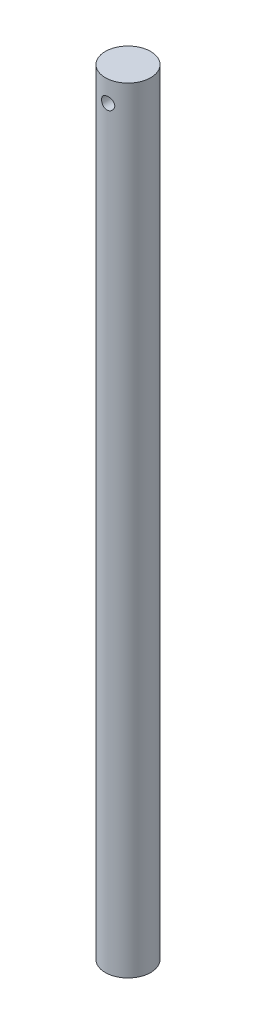
SolidWorks part; units mm, degrees
ref_plane "Спереди" through (0, 0, 0) normal (0, 0, 1) x (1, 0, 0)
ref_plane "Сверху" through (0, 0, 0) normal (0, 1, 0) x (1, 0, 0)
ref_plane "Справа" through (0, 0, 0) normal (1, 0, 0) x (0, 0, -1)
sketch "Эскиз1" plane through (0, 0, 0) normal (0, 1, 0) x (1, 0, 0)
  circle A1 centre (0, 0) radius 15
  dimension "D2" = 30
extrude "Вытянуть1" add sketch "Эскиз1" along normal blind 512
sketch "Sketch1" plane through (0, 0, 42.5046) normal (0, 0, 1) x (1, 0, 0)
  circle A0 centre (1.3077, 498) radius 4
extrude "Cut-Extrude1" cut sketch "Sketch1" against normal through all
